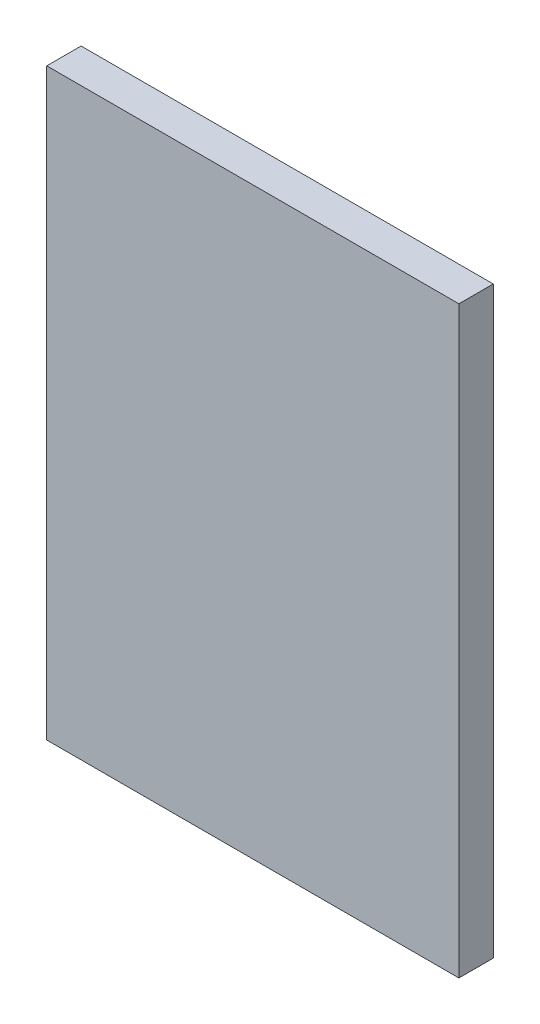
SolidWorks part; units mm, degrees
material "Pine"
ref_plane "Alzado" through (0, 0, 0) normal (0, 0, 1) x (1, 0, 0)
ref_plane "Planta" through (0, 0, 0) normal (0, 1, 0) x (1, 0, 0)
ref_plane "Vista lateral" through (0, 0, 0) normal (1, 0, 0) x (0, 0, -1)
sketch "Sketch1" plane through (0, 0, 0) normal (0, 0, 1) x (1, 0, 0)
  line L1 (-152.4, -215.9) -> (152.4, -215.9)
  line L2 (-152.4, -215.9) -> (-152.4, 215.9)
  line L3 (-152.4, 215.9) -> (152.4, 215.9)
  line L4 (152.4, -215.9) -> (152.4, 215.9)
  line L5 (-152.4, -215.9) -> (152.4, 215.9) construction
  line L6 (-152.4, 215.9) -> (152.4, -215.9) construction
  point P0 (0, 0)
  dimension "D1" = 431.8
  dimension "D2" = 304.8
extrude "Boss-Extrude1" add sketch "Sketch1" along normal blind 25.4
